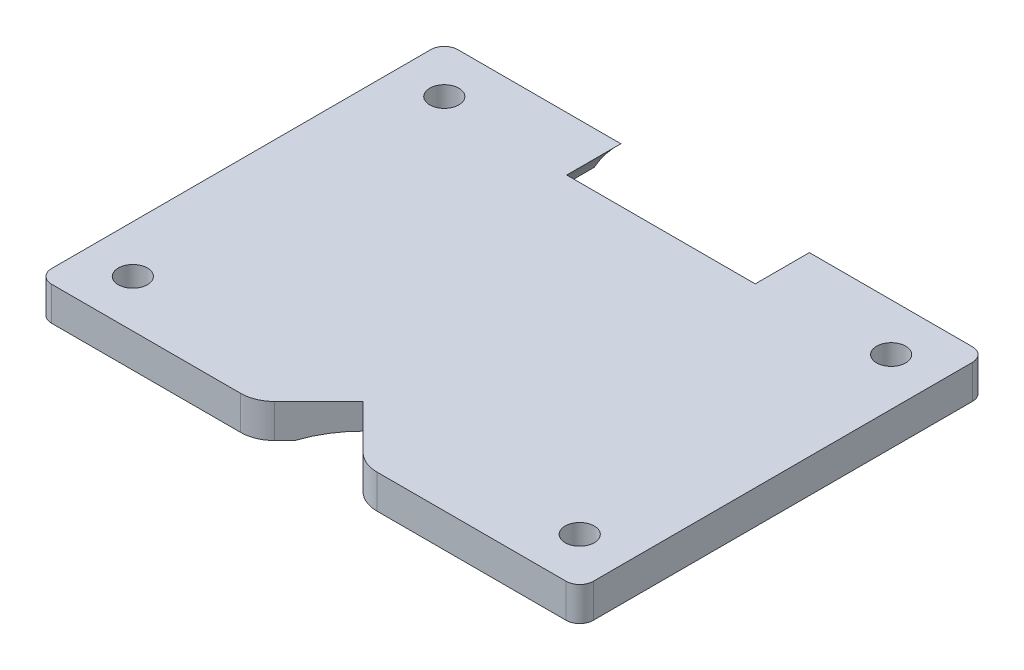
SolidWorks part; units mm, degrees
ref_plane "Front Plane" through (0, 0, 0) normal (0, 0, 1) x (1, 0, 0)
ref_plane "Top Plane" through (0, 0, 0) normal (0, 1, 0) x (1, 0, 0)
ref_plane "Right Plane" through (0, 0, 0) normal (1, 0, 0) x (0, 0, -1)
sketch "Sketch1" plane through (0, 0, 0) normal (0, 0, 1) x (1, 0, 0)
  line L0 (-40, 15.05) -> (40, 15.05)
  line L1 (0, 0) -> (0, 30.1) construction
  line L2 (-40, 15.05) -> (-40, 10.05)
  line L3 (-40, 10.05) -> (-14.9331, 10.05)
  line L4 (40, 15.05) -> (40, 10.05)
  line L5 (40, 10.05) -> (14.9331, 10.05)
  line L6 (-10.0248, -14.95) -> (10.0248, -14.95)
  circle A0 centre (0, 0) radius 11.25
  arc A1 (-14.9331, 10.05) -> (-10.0248, -14.95) centre (0, 0) ccw
  arc A2 (10.0248, -14.95) -> (14.9331, 10.05) centre (0, 0) ccw
  point P5 (0, 15.05)
  dimension "D1" = 22.5
  dimension "D3" = 15.05
  dimension "D4" = 36
  dimension "D2" = 80
  dimension "D5" = 5
  dimension "D6" = 5
  dimension "D7" = 30
extrude "Boss-Extrude1" add sketch "Sketch1" along normal blind 60
sketch "Sketch6" plane through (0, 10.05, 0) normal (0, -1, 0) x (-1, 0, 0)
  line L0 (33, -60) -> (33, 0) construction
  line L1 (40, 0) -> (14.9331, 0) construction
  line L2 (-33, -60) -> (-33, 0) construction
  line L3 (-14.9331, -60) -> (-40, -60) construction
  line L4 (-14.9331, 0) -> (-40, 0) construction
  line L5 (40, -60) -> (40, 0) construction
  line L6 (-40, -60) -> (-40, 0) construction
  line L7 (40, -60) -> (14.9331, -60) construction
  circle A0 centre (33, -53) radius 2.15
  circle A1 centre (33, -7) radius 2.15
  circle A2 centre (-33, -53) radius 2.15
  circle A3 centre (-33, -7) radius 2.15
  dimension "D3" = 4.3
  dimension "D4" = 4.3
  dimension "D5" = 4.3
  dimension "D6" = 4.3
  dimension "D7" = 7
  dimension "D8" = 7
  dimension "D9" = 7
  dimension "D10" = 7
  dimension "D1" = 7
  dimension "D2" = 7
extrude "Cut-Extrude5" cut sketch "Sketch6" against normal through all
sketch "Sketch7" plane through (0, 0, 60) normal (0, 0, 1) x (1, 0, 0)
  line L0 (-14.9331, 10.05) -> (14.9331, 10.05)
  arc A0 (-14.9331, 10.05) -> (14.9331, 10.05) centre (0, 0) ccw
extrude "Cut-Extrude6" cut sketch "Sketch7" against normal blind 25
fillet "Fillet3" radius 2 4 edges at (40, 12.55, 0) (-40, 12.55, 0) (-40, 12.55, 60) (40, 12.55, 60)
sketch "Sketch8" plane through (0, 15.05, 0) normal (0, 1, 0) x (1, 0, 0)
  line L0 (0, 0) -> (0, -60) construction
  line L1 (38, -60) -> (-38, -60) construction
  line L2 (0, -52) -> (8, -60)
  line L3 (8, -60) -> (-8, -60)
  line L4 (-8, -60) -> (0, -52)
  dimension "D1" = 45
  dimension "D2" = 45
  dimension "D3" = 8
extrude "Cut-Extrude7" cut sketch "Sketch8" against normal through all
fillet "Fillet5" radius 5 2 edges at (8, 12.55, 60) (-8, 12.55, 60)
sketch "Sketch9" plane through (0, 0, 0) normal (0, 0, -1) x (-1, 0, 0)
  circle A0 centre (0, 0) radius 20.5
  dimension "D1" = 41
extrude "Cut-Extrude8" cut sketch "Sketch9" against normal blind 8
sketch "Sketch10" plane through (0, 0, 8) normal (0, 0, -1) x (-1, 0, 0)
  line L0 (-13.9193, 15.05) -> (13.9193, 15.05)
  line L1 (-14.0267, -14.95) -> (14.0267, -14.95)
  arc A0 (-13.9193, 15.05) -> (-14.0267, -14.95) centre (0, 0) ccw
  arc A1 (14.0267, -14.95) -> (13.9193, 15.05) centre (0, 0) ccw
  circle A2 centre (0, 0) radius 11.25
  circle A3 centre (0, 0) radius 11.25 construction
  dimension "D1" = 30
extrude "Boss-Extrude2" add sketch "Sketch10" against normal blind 8
sketch "Sketch11" plane through (0, 0, 8) normal (0, 0, -1) x (-1, 0, 0)
  line L0 (0, 0) -> (-16, 0) construction
  line L1 (0, 0) -> (-11.3137, 11.3137) construction
  circle A0 centre (0, 0) radius 16 construction
  point P3 (-16, 0)
  point P4 (0, 0)
  point P5 (0, 16)
  point P6 (-11.3137, 11.3137)
  point P7 (0, 0)
  point P8 (11.3137, 11.3137)
  point P9 (16, 0)
  point P10 (11.3137, -11.3137)
  point P12 (-11.3137, -11.3137)
  point P16 (0, -16)
  dimension "D1" = 32
  dimension "D3" = 45
  dimension "D2" = 8
sketch "Sketch12" plane through (0, 0, 8) normal (0, 0, -1) x (-1, 0, 0)
  circle A0 centre (-16, 0) radius 1.65
  circle A1 centre (-11.3137, 11.3137) radius 1.65
  circle A2 centre (-11.3137, -11.3137) radius 1.65
  circle A3 centre (11.3137, -11.3137) radius 1.65
  circle A4 centre (16, 0) radius 1.65
  circle A5 centre (11.3137, 11.3137) radius 1.65
  dimension "D1" = 3.3
  dimension "D2" = 3.3
  dimension "D3" = 3.3
  dimension "D4" = 3.3
  dimension "D5" = 3.3
  dimension "D6" = 3.3
extrude "Cut-Extrude9" cut sketch "Sketch12" against normal blind 14
fillet "Fillet7" radius 5 2 edges at (17.8675, 10.05, 12) (-17.8675, 10.05, 12)
fillet "Fillet8" radius 3 2 edges at (14.9331, 10.05, 25.5) (-14.9331, 10.05, 25.5)
